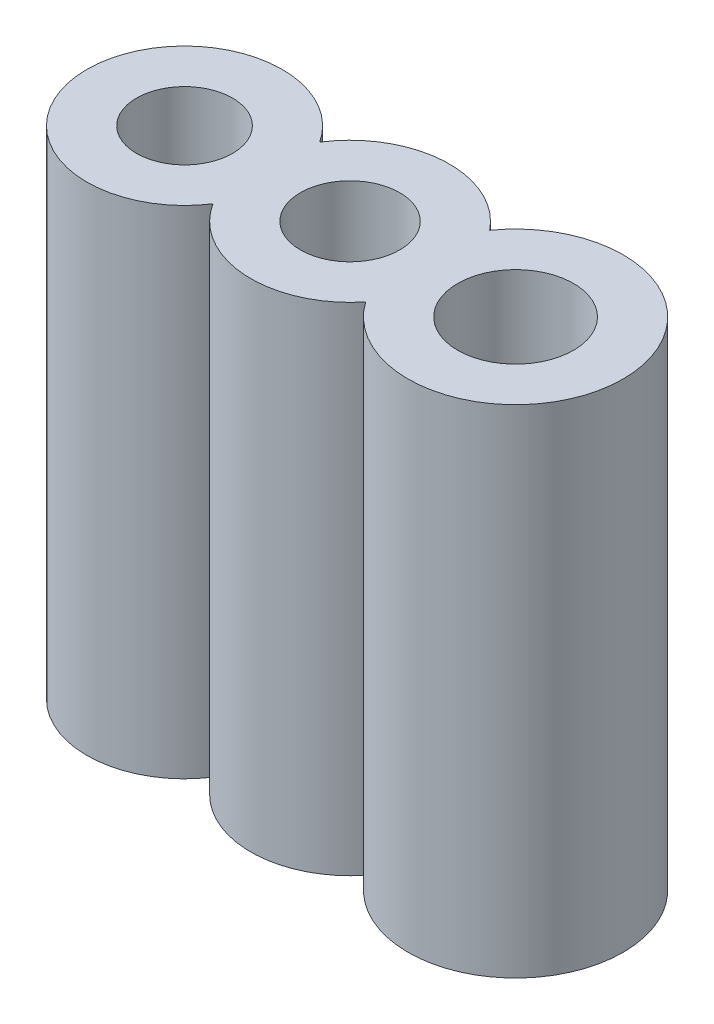
SolidWorks part; units mm, degrees
ref_plane "Front Plane" through (0, 0, 0) normal (0, 0, 1) x (1, 0, 0)
ref_plane "Top Plane" through (0, 0, 0) normal (0, 1, 0) x (1, 0, 0)
ref_plane "Right Plane" through (0, 0, 0) normal (1, 0, 0) x (0, 0, -1)
sketch "Sketch1" plane through (0, 0, 0) normal (0, 1, 0) x (1, 0, 0)
  line L0 (-5, 0) -> (5, 0) construction
  circle A0 centre (0, 0) radius 1.5
  circle A1 centre (5, 0) radius 1.75
  circle A2 centre (-5, 0) radius 1.45
  arc A3 (-2.5298, 1.6126) -> (-2.5298, -1.6126) centre (-5, 0) ccw
  arc A4 (-2.5298, -1.6126) -> (2.3438, -1.8727) centre (0, 0) ccw
  arc A5 (2.3438, -1.8727) -> (2.3437, 1.8727) centre (5, 0) ccw
  arc A6 (2.3437, 1.8727) -> (-2.5298, 1.6126) centre (0, 0) ccw
  circle A7 centre (0, 0) radius 3 construction
  circle A8 centre (-5, 0) radius 2.95 construction
  circle A9 centre (5, 0) radius 3.25 construction
  point P3 (0, 0)
  point P9 (9.255, 0)
  point P14 (3.25, 0)
  point P16 (-2.8, 0)
  dimension "D1" = 2.9
  dimension "D2" = 3
  dimension "D3" = 3.5
  dimension "D4" = 5
  dimension "D5" = 1.5
extrude "Boss-Extrude1" add sketch "Sketch1" along normal blind 15
